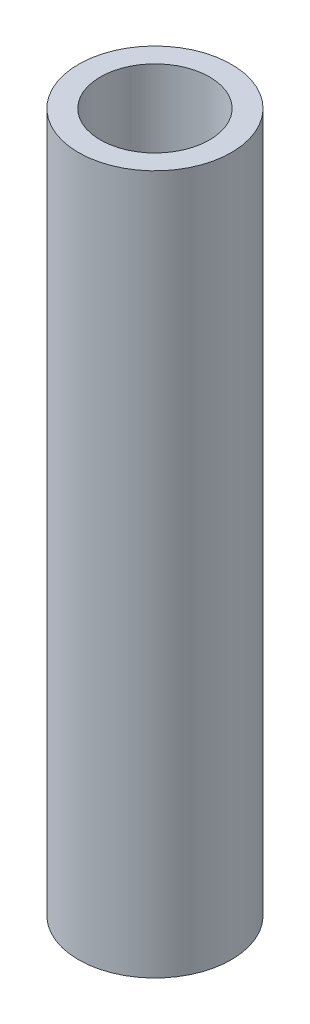
SolidWorks part; units mm, degrees
ref_plane "Front Plane" through (0, 0, 0) normal (0, 0, 1) x (1, 0, 0)
ref_plane "Top Plane" through (0, 0, 0) normal (0, 1, 0) x (1, 0, 0)
ref_plane "Right Plane" through (0, 0, 0) normal (1, 0, 0) x (0, 0, -1)
sketch "Sketch1" plane through (0, 0, 0) normal (0, 1, 0) x (1, 0, 0)
  circle A0 centre (0, 0) radius 2.5
  circle A1 centre (0, 0) radius 3.5
  dimension "D1" = 5
  dimension "D2" = 7
extrude "Boss-Extrude1" add sketch "Sketch1" along normal blind 32 contours A1
sketch "Sketch2" plane through (0, 0, 0) normal (0, -1, 0) x (1, 0, 0)
  circle A0 centre (0, 0) radius 2.5
  dimension "D1" = 5
extrude "Cut-Extrude1" cut sketch "Sketch2" against normal blind 32
